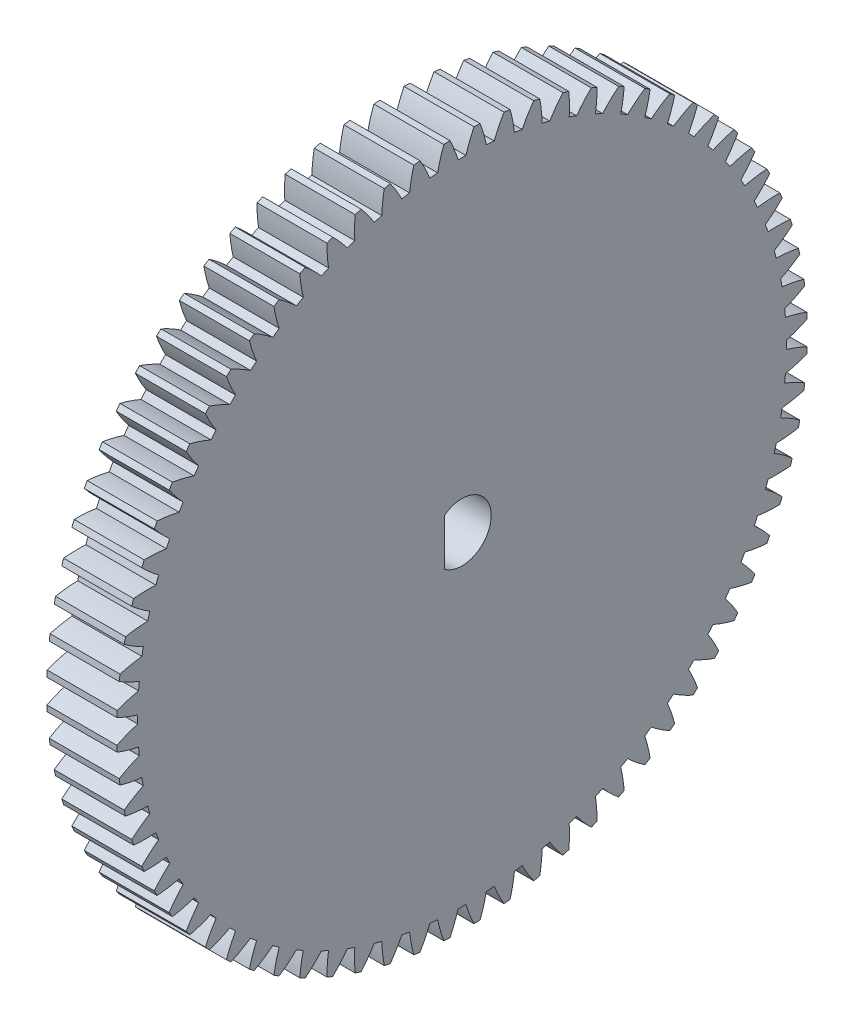
SolidWorks part; units mm, degrees
ref_plane "Plane1" through (0, 0, 0) normal (0, 0, 1) x (1, 0, 0)
ref_plane "Plane2" through (0, 0, 0) normal (0, 1, 0) x (1, 0, 0)
ref_plane "Plane3" through (0, 0, 0) normal (1, 0, 0) x (0, 0, -1)
sketch "HoldingSke" plane through (0, 0, 0) normal (0, 1, 0) x (1, 0, 0)
  line L0 (0, 0) -> (0.3863, -1.1888)
  line L1 (-15, 0) -> (100, 0) construction
  line L2 (0, 0) -> (-2.1039, 2.3779)
  line L3 (0, 0) -> (-11.863, 4.5341)
  line L4 (0, 0) -> (2.6687, 8.2133)
  line L5 (0, 0) -> (-46.8476, -17.4728)
  line L6 (0, 0) -> (-9.9476, -6.7116)
  line L7 (-2.1039, 2.3779) -> (8.6586, 51.206)
  line L8 (-76.2, 54.61) -> (-75.3, 54.61)
  line L9 (-71.009, 38.7566) -> (-53.1078, 45.2721)
  line L10 (-76.2, 71.12) -> (104.1128, 71.12)
  line L11 (0, 0) -> (-12, 0)
  line L12 (-76.2, 101.6) -> (-76.17, 101.6)
  line L13 (24.9733, 27.94) -> (52.9518, 28.4284)
  line L14 (24.9733, 27.94) -> (24.9743, 27.94)
  line L15 (24.9733, 27.94) -> (100.4006, 29.5858)
  line L16 (-63.627, -0.8) -> (-12.827, -0.8)
  circle A0 centre (0, 0) radius 2.5
  circle A1 centre (0, 0) radius 27.799
  circle A2 centre (0, 0) radius 37.5
  circle A3 centre (0, 0) radius 2.5
  dimension "MHD" = 55.598
  dimension "Hub_dia" = 75
  dimension "Bore" = 5
  dimension "MBD" = 5
  dimension "Num_teeth" = 72
  dimension "Pitch" = 1.25
  dimension "Overall_len" = 50
  dimension "Show_teeth" = 72
  dimension "Thickness" = 12
  dimension "OAL" = 50.0002
  dimension "T_dim" = 0.9
  dimension "Ap" = 20
  dimension "H" = 19.05
  dimension "Pitch_radius" = 180.3128
  dimension "Width" = 12
  dimension "Backlash" = 0.03
  dimension "Addendum_fac" = 1
  dimension "Dedendum_fac" = 1.25
  dimension "Clearance_fac" = 0.25
  dimension "Dedendum_add" = 0.001
  dimension "Module" = 0.8
sketch "BasProSke" plane through (0, 0, 0) normal (0, 1, 0) x (1, 0, 0)
  line L0 (-10, 0) -> (60, 0) construction
  line L1 (0, 0) -> (0, 29.6)
  line L2 (0, 0) -> (6, 0)
  line L3 (6, 0) -> (6, 29.6)
  line L4 (6, 29.6) -> (0, 29.6)
  dimension "Thickness" = 6
  dimension "Diameter" = 59.2
revolve "Base-Revolve" add sketch "BasProSke" angle 360 about L0
sketch "TooCutSke" plane through (0, 0, 0) normal (1, 0, 0) x (0, 0, -1)
  line L1 (0, 0) -> (0, 107) construction
  line L2 (0, 0) -> (-0.6808, 28.792) construction
  line L3 (0, 0) -> (-2.512, 57.5337) construction
  line L4 (-0.6808, 28.792) -> (-1.256, 28.7668) construction
  arc A0 (0.3383, 27.7969) -> (-0.3383, 27.7969) centre (0, 0) ccw
  arc A1 (1.0408, 29.6071) -> (-1.0408, 29.6071) centre (0, 0) ccw
  circle A2 centre (0, 0) radius 28.8 construction
  circle A3 centre (0, 0) radius 27.0631 construction
  arc A4 (-0.3383, 27.7969) -> (-1.0408, 29.6071) centre (-11.391, 24.5491) ccw
  arc A5 (1.0408, 29.6071) -> (0.3383, 27.7969) centre (11.391, 24.5491) ccw
  dimension "Root_dia" = 55.598
  dimension "Overcut_dia" = 59.2508
  dimension "Pitch_dia" = 57.6
  dimension "Base_dia" = 54.1263
  dimension "Flank_rad" = 11.52
  dimension "Half_ang" = 2.5
  dimension "Half_CT" = 0.5758
extrude "ToothCut" cut sketch "TooCutSke" along normal through all
fillet "Breaks" [suppressed] radius 0.016
fillet "RootFillets" [suppressed] radius 0.201
pattern_circular "TeethCuts" count 72 every 5 about axis through (-10, 0, 0) along (1, 0, 0) of "ToothCut", "RootFillets", "Breaks"
sketch "HubNeaOneSke" plane through (0, 0, 0) normal (-1, 0, 0) x (0, 0, 1)
  circle A0 centre (0, 0) radius 27.799
  dimension "Diameter" = 55.598
extrude "HubNearOne" [suppressed] add sketch "HubNeaOneSke" along normal blind 44.0002
sketch "HubNeaBotSke" plane through (0, 0, 0) normal (-1, 0, 0) x (0, 0, 1)
  circle A0 centre (0, 0) radius 27.799
  dimension "Diameter" = 55.598
extrude "HubNearBoth" [suppressed] add sketch "HubNeaBotSke" along normal blind 22.0001
ref_plane "FarPln" through (6, 0, 0) normal (1, 0, 0) x (0, 0, -1)
sketch "HubFarSke" plane through (6, 0, 0) normal (1, 0, 0) x (0, 0, -1)
  circle A0 centre (0, 0) radius 27.799
  dimension "Diameter" = 55.598
extrude "HubFar" [suppressed] add sketch "HubFarSke" along normal blind 22.0001
sketch "BorSke" plane through (0, 0, 0) normal (1, 0, 0) x (0, 0, -1)
  circle A0 centre (0, 0) radius 2.5
  dimension "Diameter" = 5
extrude "Bore" cut sketch "BorSke" along normal mid plane 100.0003
sketch "KeySke" plane through (0, 0, 0) normal (1, 0, 0) x (0, 0, -1)
  line L0 (-1, 0) -> (-1, 3.4)
  line L1 (-1, 3.4) -> (1, 3.4)
  line L2 (1, 3.4) -> (1, 0)
  line L3 (0, 0) -> (0, 34) construction
  line L4 (-1, 0) -> (1, 0)
  dimension "Offset" = 3.4
  dimension "Width" = 2
extrude "Keyway" [suppressed] cut sketch "KeySke" along normal mid plane 100.0003
pattern_circular "Keyway2" [suppressed] count 2 every 90 about axis through (-10, 0, 0) along (1, 0, 0)
sketch "Sketch1" plane through (6, 0, 0) normal (1, 0, 0) x (0, 0, -1)
  line L0 (-2.5, 0) -> (-1.5, 0) construction
  line L1 (-1.5, 2) -> (-1.5, -2)
  circle A0 centre (0, 0) radius 2.5 construction
  arc A1 (-1.5, 2) -> (-1.5, -2) centre (0, 0) ccw
  point P9 (-1.5, 0)
extrude "Boss-Extrude1" add sketch "Sketch1" against normal blind 6 contours A1 L0 L1 | L0 A1 L1
equation "' \"Module@HoldingSke\" = 6.35"
equation "' \"Num_teeth@HoldingSke\" = 12"
equation "' \"Ap@HoldingSke\" =  20"
equation "' \"Ap@HoldingSke\" = 20"
equation "' \"Width@HoldingSke\" = 0.5 * 25.4"
equation "' \"Hub_dia@HoldingSke\"= 1 * 25.4"
equation "' \"Hub_dia@HoldingSke\" = 1 * 25.4"
equation "' \"Overall_len@HoldingSke\" = 1.0 * 25.4"
equation "' \"Bore@HoldingSke\" = 0.75 * 25.4"
equation "' \"T_dim@HoldingSke\" = 0.1 * 25.4"
equation "' \"Width@KeySke\" = 0.25 * 25.4"
equation "' \"Show_teeth@HoldingSke\" = 13"
equation "' \"Backlash@HoldingSke\" = 0.009 * 25.4"
equation "' \"Addendum_fac@HoldingSke\" = 1.0"
equation "' \"Dedendum_fac@HoldingSke\" = 1.25"
equation "' \"Dedendum_add@HoldingSke\" = 0.00005 * 25.4"
equation "' \"Clearance_fac@HoldingSke\" = 0.25"
equation "\"Pitch@HoldingSke\" = 1 / \"Module@HoldingSke\""
equation "\"Overcut_dia@TooCutSke\" = (\"Num_teeth@HoldingSke\" + 2 * \"Addendum_fac@HoldingSke\") / \"Pitch@HoldingSke\" + 0.002 * 25.4"
equation "\"Pitch_dia@TooCutSke\" = \"Num_teeth@HoldingSke\" / \"Pitch@HoldingSke\""
equation "\"Base_dia@TooCutSke\" = \"Num_teeth@HoldingSke\" / \"Pitch@HoldingSke\" * cos((\"Ap@HoldingSke\"  * 3.14159265 / 180))"
equation "\"Root_dia@TooCutSke\" = (\"Num_teeth@HoldingSke\" + 2) / \"Pitch@HoldingSke\" - 2 * (\"Addendum_fac@HoldingSke\" + \"Dedendum_fac@HoldingSke\") / \"Pitch@HoldingSke\" - \"Dedendum_add@HoldingSke\" * 2"
equation "\"Half_ang@TooCutSke\" = 180 / \"Num_teeth@HoldingSke\""
equation "\"Half_CT@TooCutSke\" = \"Num_teeth@HoldingSke\" / \"Pitch@HoldingSke\" * sin((3.14159265 / 2 / \"Num_teeth@HoldingSke\")) / 2 - 7 * \"Backlash@HoldingSke\" / 4"
equation "\"Flank_rad@TooCutSke\" = \"Num_teeth@HoldingSke\" / \"Pitch@HoldingSke\" / 5"
equation "\"Radius@RootFillets\" = \"Clearance_fac@HoldingSke\" / \"Pitch@HoldingSke\" + \"Dedendum_add@HoldingSke\""
equation "\"Break_rad@Breaks\" = 0.02 / \"Pitch@HoldingSke\""
equation "\"Thickness@HoldingSke\" = \"Width@HoldingSke\""
equation "\"OAL@HoldingSke\" = \"Thickness@HoldingSke\""
equation "\"MHD@HoldingSke\" = (\"Num_teeth@HoldingSke\" + 2) / \"Pitch@HoldingSke\" - 2 * (\"Addendum_fac@HoldingSke\" + \"Dedendum_fac@HoldingSke\")  / \"Pitch@HoldingSke\" - \"Dedendum_add@HoldingSke\" * 2"
equation "\"MBD@HoldingSke\" = (\"Num_teeth@HoldingSke\" + 2) / \"Pitch@HoldingSke\" - 2 * (\"Addendum_fac@HoldingSke\" + \"Dedendum_fac@HoldingSke\")  / \"Pitch@HoldingSke\" - \"Dedendum_add@HoldingSke\" * 2 - 0.002 * 25.4"
equation "\"MHD@HoldingSke\" = ((sgn( \"MHD@HoldingSke\" - \"Hub_dia@HoldingSke\" )-1)*( \"MHD@HoldingSke\" - \"Hub_dia@HoldingSke\" ))/-2+ \"Hub_dia@HoldingSke\""
equation "\"MBD@HoldingSke\" = ((sgn( \"MBD@HoldingSke\" - \"Bore@HoldingSke\" )-1)*( \"MBD@HoldingSke\" - \"Bore@HoldingSke\" ))/-2+ \"Bore@HoldingSke\""
equation "\"OAL@HoldingSke\" = ((sgn( \"OAL@HoldingSke\" - \"Overall_len@HoldingSke\" )+1)*( \"OAL@HoldingSke\" - \"Overall_len@HoldingSke\" ))/2 + \"Overall_len@HoldingSke\" + 0.000002 * 25.4"
equation "\"Num_teeth@TeethCuts\" = int( \"Show_teeth@HoldingSke\" ) + 1"
equation "\"Num_teeth@TeethCuts\" = ((sgn( \"Num_teeth@TeethCuts\" - \"Num_teeth@HoldingSke\" )-1)*( \"Num_teeth@TeethCuts\" - \"Num_teeth@HoldingSke\" ))/-2+ \"Num_teeth@HoldingSke\""
equation "\"Num_teeth@TeethCuts\" = ((sgn( \"Num_teeth@TeethCuts\" - 2.0)+1)*( \"Num_teeth@TeethCuts\" - 2.0))/2 +2.0"
equation "\"Angle@TeethCuts\" = 360.0 / \"Num_teeth@HoldingSke\""
equation "\"Diameter@BasProSke\" = (\"Num_teeth@HoldingSke\" + 2 * \"Addendum_fac@HoldingSke\") / \"Pitch@HoldingSke\""
equation "\"Thickness@BasProSke\"= 6"
equation "' \"Fillet_rad@BasProSke\" =  \"Thickness@HoldingSke\" * 0.05"
equation "' \"Fillet_rad@BasProSke\" = \"Thickness@HoldingSke\" * 0.05"
equation "\"MHD@HoldingSke\" = ((sgn( \"MHD@HoldingSke\" - \"Root_dia@TooCutSke\" )-1)*( \"MHD@HoldingSke\" - \"Root_dia@TooCutSke\" ))/-2+ \"Root_dia@TooCutSke\""
equation "\"Diameter@HubNeaOneSke\" = \"MHD@HoldingSke\""
equation "\"Length@HubNearOne\" = \"OAL@HoldingSke\" - \"Thickness@BasProSke\""
equation "\"Diameter@HubNeaBotSke\" = \"MHD@HoldingSke\""
equation "\"Length@HubNearBoth\" = ( \"OAL@HoldingSke\" - \"Thickness@BasProSke\" ) / 2.0"
equation "\"Thickness@FarPln\" = \"Thickness@BasProSke\""
equation "\"Diameter@HubFarSke\" = \"MHD@HoldingSke\""
equation "\"Length@HubFar\" = ( \"OAL@HoldingSke\" - \"Thickness@BasProSke\" ) / 2.0"
equation "\"Diameter@BorSke\" = \"MBD@HoldingSke\""
equation "\"D1@Bore\" = \"OAL@HoldingSke\" * 2.0"
equation "\"D1@Keyway\" = \"OAL@HoldingSke\" * 2.0"
equation "\"Offset@KeySke\" = \"T_dim@HoldingSke\" + \"MBD@HoldingSke\" / 2.0"
